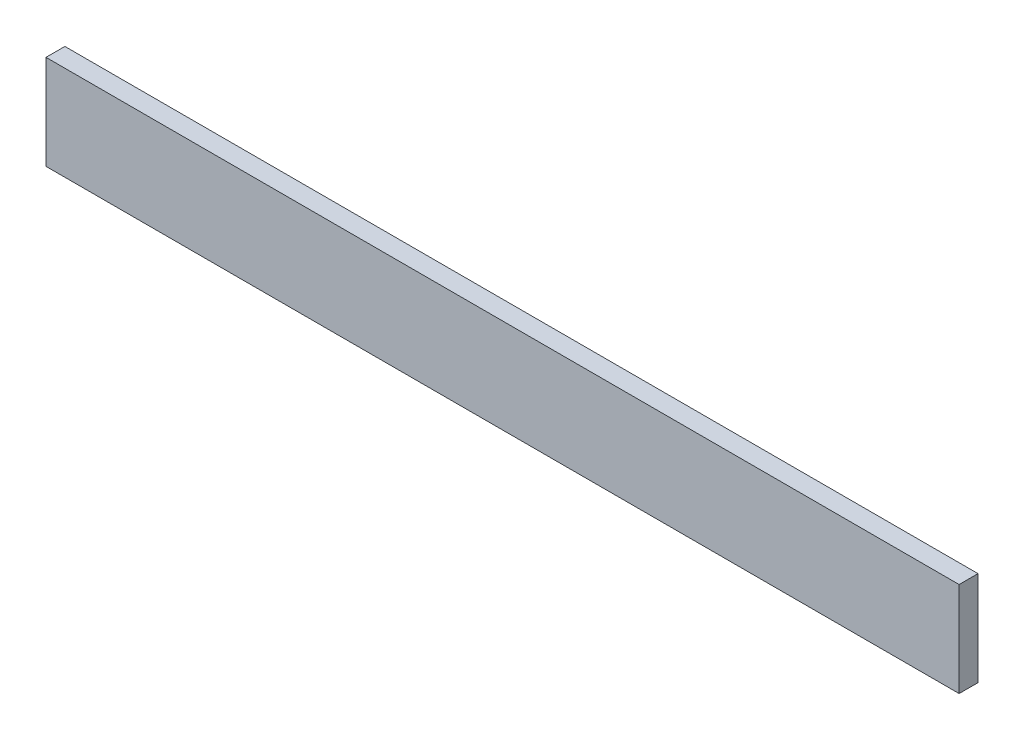
SolidWorks part; units mm, degrees
ref_plane "前视基准面" through (0, 0, 0) normal (0, 0, 1) x (1, 0, 0)
ref_plane "上视基准面" through (0, 0, 0) normal (0, 1, 0) x (1, 0, 0)
ref_plane "右视基准面" through (0, 0, 0) normal (1, 0, 0) x (0, 0, -1)
other "Configuration Table"
sketch "草图1" plane through (0, 0, 120.0175) normal (0, 0, -1) x (-1, 0, 0)
  line L1 (-39.6217, 39.0354) -> (57.0532, 39.0354)
  line L2 (-39.6217, 39.0354) -> (-39.6217, 29.0354)
  line L3 (-39.6217, 29.0354) -> (57.0532, 29.0354)
  line L4 (57.0532, 39.0354) -> (57.0532, 29.0354)
  line L5 (-40.6217, -34.9394) -> (-40.6217, 39.0354) construction
  line L6 (58.0532, 39.0354) -> (58.0532, -34.9394) construction
  line L7 (68.0532, 39.0354) -> (58.0532, 39.0354) construction
  dimension "D1" = 1
  dimension "D2" = 1
  dimension "D3" = 10
extrude "凸台-拉伸1" add sketch "草图1" along normal blind 2
